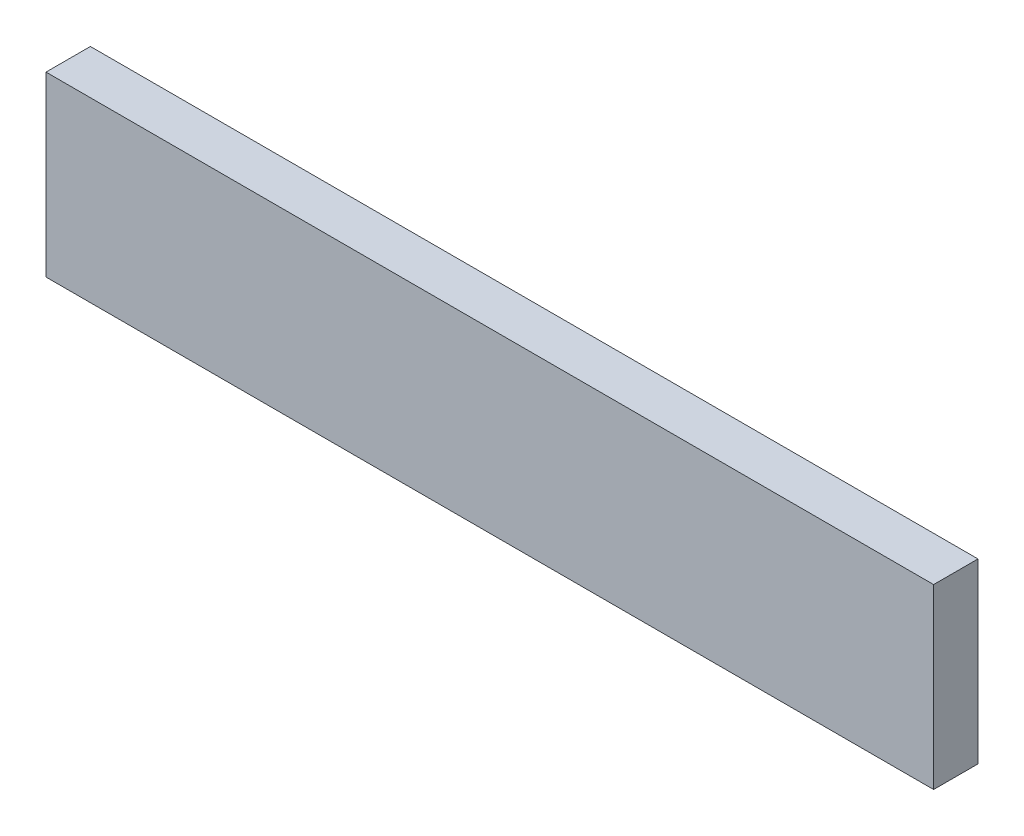
SolidWorks part; units mm, degrees
ref_plane "Front Plane" through (0, 0, 0) normal (1, 0, 0) x (0, 1, 0)
ref_plane "Top Plane" through (0, 0, 0) normal (0, 0, 1) x (0, 1, 0)
ref_plane "Right Plane" through (0, 0, 0) normal (0, 1, 0) x (-1, 0, 0)
sketch "Sketch1" plane through (0, 0, 0) normal (0, 0, 1) x (0, 1, 0)
  line L1 (-10000, 0) -> (10000, 0)
  line L2 (-10000, 0) -> (-10000, -100000)
  line L3 (-10000, -100000) -> (10000, -100000)
  line L4 (10000, 0) -> (10000, -100000)
  point P4 (0, 0)
  dimension "D1" = 20000
  dimension "D2" = 100000
extrude "Boss-Extrude1" add sketch "Sketch1" along normal blind 5000
